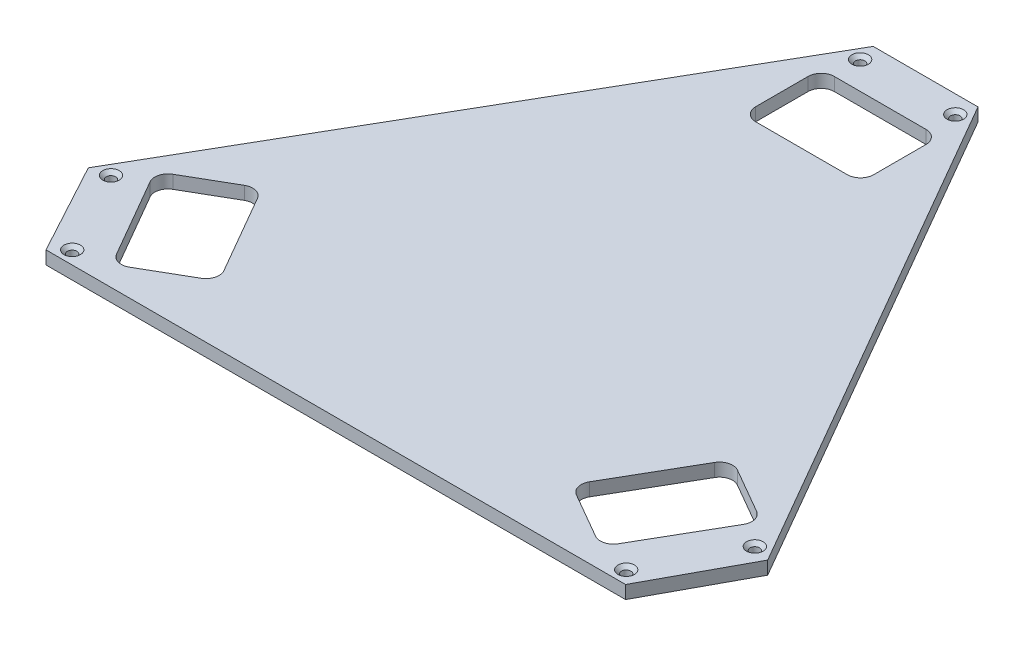
SolidWorks part; units mm, degrees
ref_plane "Plan de face" through (0, 0, 0) normal (0, 0, 1) x (1, 0, 0)
ref_plane "Plan de dessus" through (0, 0, 0) normal (0, 1, 0) x (1, 0, 0)
ref_plane "Plan de droite" through (0, 0, 0) normal (1, 0, 0) x (0, 0, -1)
sketch "Esquisse1" plane through (0, 0, 0) normal (0, 1, 0) x (1, 0, 0)
  line L0 (0, 46.0354) -> (0, -213.7722) construction
  line L1 (-32.5, -10.2563) -> (-117.5, -157.4806)
  line L2 (-85, -213.7722) -> (85, -213.7722)
  line L3 (117.5, -157.4806) -> (32.5, -10.2563)
  line L4 (0, 46.0354) -> (0, -103.9646) construction
  line L5 (0, 46.0354) -> (0, 106.0354) construction
  line L6 (-32.5, 49.7437) -> (-32.5, -10.2563)
  line L7 (-150, -213.7722) -> (-201.9615, -243.7722) construction
  line L8 (0, 106.0354) -> (-32.5, 49.7437) construction
  line L10 (32.5, 49.7437) -> (0, 106.0354) construction
  line L11 (32.5, 49.7437) -> (32.5, -10.2563)
  line L12 (-169.4615, -187.4806) -> (-117.5, -157.4806)
  line L13 (0, 61.0354) -> (25.9808, 61.0354) [skipped]
  line L14 (-201.9615, -243.7722) -> (-136.9615, -243.7722) construction
  line L16 (-169.4615, -187.4806) -> (-201.9615, -243.7722) construction
  line L17 (-136.9615, -243.7722) -> (-85, -213.7722)
  line L18 (150, -213.7722) -> (201.9615, -243.7722) construction
  line L19 (-150.4525, -242.9885) -> (-163.4429, -220.4885) [skipped]
  line L20 (136.9615, -243.7722) -> (85, -213.7722)
  line L23 (169.4615, -187.4806) -> (117.5, -157.4806)
  line L24 (85, -213.7722) -> (-85, -213.7722)
  line L25 (32.5, -10.2563) -> (117.5, -157.4806)
  line L26 (-32.5, -10.2563) -> (0, 46.0354) construction
  line L27 (0, 46.0354) -> (32.5, -10.2563) construction
  line L28 (117.5, -157.4806) -> (150, -213.7722) construction
  line L29 (150, -213.7722) -> (85, -213.7722) construction
  line L30 (-85, -213.7722) -> (-150, -213.7722) construction
  line L31 (-150, -213.7722) -> (-117.5, -157.4806) construction
  line L32 (-150, -213.7722) -> (-15.7661, -136.2722) construction
  line L33 (-95.7675, -201.7057) -> (-113.2675, -171.3948)
  line L34 (0, -213.7722) -> (0, -171.4176) construction
  line L35 (-88.9374, -203.5358) -> (-71.6169, -193.5358)
  line L36 (-111.4374, -164.5647) -> (-94.1169, -154.5647)
  line L37 (-69.7867, -186.7057) -> (-87.2867, -156.3948)
  line L38 (-93.2675, -206.0358) -> (-89.7867, -152.0647) construction
  line L39 (-115.7675, -167.0647) -> (-67.2867, -191.0358) construction
  line L40 (-17.5, -35.9646) -> (17.5, -35.9646)
  line L41 (-22.5, -30.9646) -> (-22.5, -10.9646)
  line L42 (22.5, -30.9646) -> (22.5, -10.9646)
  line L43 (-17.5, -5.9646) -> (17.5, -5.9646)
  line L44 (-22.5, -35.9646) -> (22.5, -5.9646) construction
  line L45 (22.5, -35.9646) -> (-22.5, -5.9646) construction
  line L46 (115.7675, -167.0647) -> (67.2867, -191.0358) construction
  line L47 (93.2675, -206.0358) -> (89.7867, -152.0647) construction
  line L48 (150, -213.7722) -> (15.7661, -136.2722) construction
  line L49 (69.7867, -186.7057) -> (87.2867, -156.3948)
  line L50 (111.4374, -164.5647) -> (94.1169, -154.5647)
  line L51 (88.9374, -203.5358) -> (71.6169, -193.5358)
  line L52 (95.7675, -201.7057) -> (113.2675, -171.3948)
  line L53 (115.7675, -167.0647) -> (67.2867, -191.0358) construction
  line L54 (93.2675, -206.0358) -> (89.7867, -152.0647) construction
  line L55 (150, -213.7722) -> (15.7661, -136.2722) construction
  line L56 (150, -213.7722) -> (117.5, -157.4806) construction
  line L57 (85, -213.7722) -> (150, -213.7722) construction
  line L58 (169.4615, -187.4806) -> (201.9615, -243.7722) construction
  line L59 (201.9615, -243.7722) -> (136.9615, -243.7722) construction
  line L60 (150, -213.7722) -> (201.9615, -243.7722) construction
  line L61 (69.7867, -186.7057) -> (87.2867, -156.3948)
  line L62 (111.4374, -164.5647) -> (94.1169, -154.5647)
  line L63 (88.9374, -203.5358) -> (71.6169, -193.5358)
  line L64 (95.7675, -201.7057) -> (113.2675, -171.3948)
  line L65 (136.9615, -243.7722) -> (85, -213.7722)
  line L66 (169.4615, -187.4806) -> (117.5, -157.4806)
  circle A0 centre (0, 76.0354) radius 15 construction
  circle A1 centre (-175.9808, -228.7722) radius 15 construction
  circle A2 centre (175.9808, -228.7722) radius 15 construction
  arc A3 (17.5, -35.9646) -> (22.5, -30.9646) centre (17.5, -30.9646) ccw
  arc A4 (22.5, -10.9646) -> (17.5, -5.9646) centre (17.5, -10.9646) ccw
  arc A5 (-22.5, -10.9646) -> (-17.5, -5.9646) centre (-17.5, -10.9646) cw
  arc A6 (-22.5, -30.9646) -> (-17.5, -35.9646) centre (-17.5, -30.9646) ccw
  arc A7 (-71.6169, -193.5358) -> (-69.7867, -186.7057) centre (-74.1169, -189.2057) ccw
  arc A8 (-88.9374, -203.5358) -> (-95.7675, -201.7057) centre (-91.4374, -199.2057) cw
  arc A9 (-87.2867, -156.3948) -> (-94.1169, -154.5647) centre (-91.6169, -158.8948) ccw
  arc A10 (-111.4374, -164.5647) -> (-113.2675, -171.3948) centre (-108.9374, -168.8948) ccw
  arc A11 (111.4374, -164.5647) -> (113.2675, -171.3948) centre (108.9374, -168.8948) cw
  arc A12 (87.2867, -156.3948) -> (94.1169, -154.5647) centre (91.6169, -158.8948) cw
  arc A13 (88.9374, -203.5358) -> (95.7675, -201.7057) centre (91.4374, -199.2057) ccw
  arc A14 (71.6169, -193.5358) -> (69.7867, -186.7057) centre (74.1169, -189.2057) cw
  arc A15 (-163.0385, -183.7722) -> (-130.5385, -240.0639) centre (-150, -213.7722) ccw
  circle A16 centre (175.9808, -228.7722) radius 15 construction
  arc A17 (163.0385, -183.7722) -> (130.5385, -240.0639) centre (150, -213.7722) cw
  arc A18 (111.4374, -164.5647) -> (113.2675, -171.3948) centre (108.9374, -168.8948) cw
  arc A19 (87.2867, -156.3948) -> (94.1169, -154.5647) centre (91.6169, -158.8948) cw
  arc A20 (88.9374, -203.5358) -> (95.7675, -201.7057) centre (91.4374, -199.2057) ccw
  arc A21 (71.6169, -193.5358) -> (69.7867, -186.7057) centre (74.1169, -189.2057) cw
  arc A22 (32.5, 42.327) -> (-32.5, 42.327) centre (0, 46.0354) ccw
  point P32 (-91.5271, -179.0502)
  point P33 (0, -20.9646)
  point P88 (91.5271, -179.0502)
  dimension "D20" = 5
  dimension "D1" = 60
  dimension "D2" = 300
  dimension "D3" = 30
  dimension "D4" = 150
  dimension "D5" = 30
  dimension "D6" = 60
  dimension "D7" = 150
  dimension "D8" = 150
  dimension "D9" = 155
  dimension "D10" = 65
  dimension "D11" = 65
  dimension "D12" = 65
  dimension "D13" = 90
  dimension "D14" = 72
  dimension "D15" = 30
  dimension "D16" = 68
  dimension "D17" = 30
  dimension "D18" = 45
  dimension "D19" = 45
extrude "Boss.-Extru.1" add sketch "Esquisse1" along normal blind 5
sketch "Esquisse2" plane through (0, 5, 0) normal (0, 1, 0) x (1, 0, 0)
  line L0 (-105.6258, -203.7722) -> (-105.6258, -213.7722) construction
  line L4 (-32.5, -10.2563) -> (-117.5, -157.4806) construction
  line L6 (-110.6258, -208.7722) -> (-105.6258, -208.7722) construction
  line L8 (-104.5175, -186.5502) -> (-178.3285, -230.1277) construction
  line L10 (0, -5.9646) -> (0, 78.7463) construction
  line L14 (-85, -213.7722) -> (-150.6258, -213.7722) construction
  line L15 (-117.5, -157.4806) -> (-149.6764, -213.2117) construction
  line L19 (-100.6258, -213.7722) -> (-110.6258, -213.7722)
  line L20 (-100.6258, -213.7722) -> (-100.6258, -203.7722)
  line L21 (122.7215, -176.5244) -> (120.2215, -172.1943) construction
  line L22 (118.3914, -179.0244) -> (127.0516, -174.0244) construction
  line L23 (117.5, -157.4806) -> (149.5516, -212.9956) construction
  line L24 (85, -213.7722) -> (150.8742, -213.7722) construction
  line L25 (201.9615, -243.7722) -> (104.5175, -186.5502) construction
  line L26 (201.9615, -243.7722) -> (104.5175, -186.5502) construction
  line L27 (110.8742, -208.7722) -> (105.8742, -208.7722) construction
  line L28 (105.8742, -203.7722) -> (105.8742, -213.7722) construction
  line L37 (-32.5, -10.2563) -> (0, 46.0354) construction
  line L38 (0, 46.0354) -> (32.5, -10.2563) construction
  line L46 (-25, 2.7341) -> (-20, 11.3944)
  line L47 (-25, 2.7341) -> (-16.3397, -2.2659)
  line L48 (-20, 11.3944) -> (-11.3397, 6.3944)
  line L49 (-16.3397, -2.2659) -> (-11.3397, 6.3944)
  line L50 (-22.5, 7.0643) -> (-13.8397, 2.0643) construction
  line L51 (-18.1699, 4.5643) -> (-15.6699, 8.8944) construction
  line L52 (18.1699, 4.5643) -> (15.6699, 8.8944) construction
  line L53 (22.5, 7.0643) -> (13.8397, 2.0643) construction
  line L54 (16.3397, -2.2659) -> (11.3397, 6.3944)
  line L55 (20, 11.3944) -> (11.3397, 6.3944)
  line L56 (25, 2.7341) -> (16.3397, -2.2659)
  line L57 (25, 2.7341) -> (20, 11.3944)
  line L58 (-110.6258, -213.7722) -> (-110.6258, -203.7722)
  line L59 (-100.6258, -203.7722) -> (-110.6258, -203.7722)
  line L64 (-124.6764, -169.9104) -> (-129.6764, -178.5707)
  line L65 (-124.6764, -169.9104) -> (-116.0161, -174.9104)
  line L66 (-129.6764, -178.5707) -> (-121.0161, -183.5707)
  line L67 (-116.0161, -174.9104) -> (-121.0161, -183.5707)
  line L68 (-118.5161, -179.2405) -> (-127.1764, -174.2405) construction
  line L69 (-122.8463, -176.7405) -> (-120.3463, -172.4104) construction
  line L70 (115.8914, -174.6943) -> (120.8914, -183.3546)
  line L71 (129.5516, -178.3546) -> (120.8914, -183.3546)
  line L72 (124.5516, -169.6943) -> (115.8914, -174.6943)
  line L73 (124.5516, -169.6943) -> (129.5516, -178.3546)
  line L74 (100.8742, -203.7722) -> (110.8742, -203.7722)
  line L75 (110.8742, -213.7722) -> (110.8742, -203.7722)
  line L76 (100.8742, -213.7722) -> (100.8742, -203.7722)
  line L77 (100.8742, -213.7722) -> (110.8742, -213.7722)
  line L78 (-17.5, -5.9646) -> (17.5, -5.9646) construction
  line L79 (-95.7675, -201.7057) -> (-113.2675, -171.3948) construction
  arc A0 (32.5, 49.7437) -> (-32.5, 49.7437) centre (0, 46.0354) ccw construction
  arc A1 (-169.4615, -187.4806) -> (-136.9615, -243.7722) centre (-150, -213.7722) ccw construction
  point P85 (-150.6258, -213.7722)
  point P86 (-149.6551, -213.1991)
  point P87 (0, 0)
  dimension "D1" = 180
  dimension "D2" = 40
  dimension "D3" = 10
  dimension "D4" = 40
  dimension "D5" = 10
  dimension "D6" = 180
  dimension "D7" = 40
  dimension "D8" = 10
  dimension "D9" = 10
  dimension "D10" = 10
  dimension "D11" = 10
hole_wizard "Fraisage pour tête fraisée bombée M31" positions "Esquisse3D1" profile "Esquisse4" countersink size "M3" standard "BSI" end condition through all
sketch3d "Esquisse3D1"
  point P14 (18.1699, 5, -4.5643)
  point P21 (-122.8463, 5, 176.7405)
  point P24 (-105.6258, 5, 208.7722)
  point P27 (-18.1699, 5, -4.5643)
  point P30 (18.1699, 5, -4.5643)
  point P32 (122.7215, 5, 176.5244)
  point P35 (105.8742, 5, 208.7722)
  point P39 (0, 0, 0)
  point P40 (0, 0, 0)
  point P41 (0, 0, 0)
  point P42 (0, 0, 0)
  point P43 (0, 0, 0)
sketch "Esquisse4" plane through (18.1699, 5, -4.5643) normal (1, 0, 0) x (0, 0, 1)
  line L0 (0, 0) -> (0, 5)
  line L1 (0, 5) -> (1.8, 5)
  line L2 (1.8, 5) -> (1.8, 1.35)
  line L3 (1.8, 1.35) -> (3.15, 0)
  line L5 (3.15, 0) -> (0, 0)
  line L6 (-1.8, 1.35) -> (-3.15, 0) construction
  line L11 (0, -6.35) -> (0, 107.95) construction
  dimension "Diamètre du perçage jusqu'au prochain" = 3.6
  dimension "Profondeur du perçage jusqu'au prochain" = 5
  dimension "Diamètre du fraisage entrant" = 6.3
  dimension "Angle du fraisage entrant" = 90
sketch "Esquisse5" plane through (0, 5, 0) normal (0, 1, 0) x (1, 0, 0)
  line L0 (-124.6764, -169.9104) -> (-100.6258, -213.7722) construction
  line L1 (-129.6764, -178.5707) -> (-110.6258, -213.7722) construction
  line L2 (-110.6258, -213.7722) -> (-85, -213.7722) construction
  line L3 (-117.5, -157.4806) -> (-129.6764, -178.5707)
  line L4 (-129.6764, -178.5707) -> (-110.6258, -213.7722)
  line L5 (-110.6258, -213.7722) -> (-85, -213.7722)
  line L6 (0, 78.7463) -> (0, -213.7722) construction
  line L7 (-85, -213.7722) -> (85, -213.7722) construction
  line L8 (-32.5, -10.2563) -> (-20, 11.3944)
  line L9 (-20, 11.3944) -> (20, 11.3944)
  line L10 (117.5, -157.4806) -> (129.6764, -178.5707)
  line L11 (129.6764, -178.5707) -> (110.6258, -213.7722)
  line L12 (110.6258, -213.7722) -> (85, -213.7722)
  line L13 (0, 78.7463) -> (0, 98.7031) construction
  line L14 (32.5, -10.2563) -> (20, 11.3944)
  spline S0 degree 3 poles (-117.5, -157.4806) (-151.9407, -148.613) (-277.0377, -222.5606) (-150.4508, -316.4145) (-56.4204, -257.1052) (-85, -213.7722) knots 0 0 0 0 0.411815 0.638485 1 1 1 1
  spline S1 degree 3 poles (117.5, -157.4806) (151.9407, -148.613) (277.0377, -222.5606) (150.4508, -316.4145) (56.4204, -257.1052) (85, -213.7722) knots 0 0 0 0 0.411815 0.638485 1 1 1 1
  spline S2 degree 2 poles (0, 98.7031) (-74.8212, 66.7891) (-32.5, -10.2563) knots 0 0 0 1 1 1
  spline S3 degree 2 poles (0, 98.7031) (74.8212, 66.7891) (32.5, -10.2563) knots 0 0 0 1 1 1
  point P39 (0, 11.3944)
extrude "Enlèv. mat.-Extru.1" cut sketch "Esquisse5" against normal blind 10
